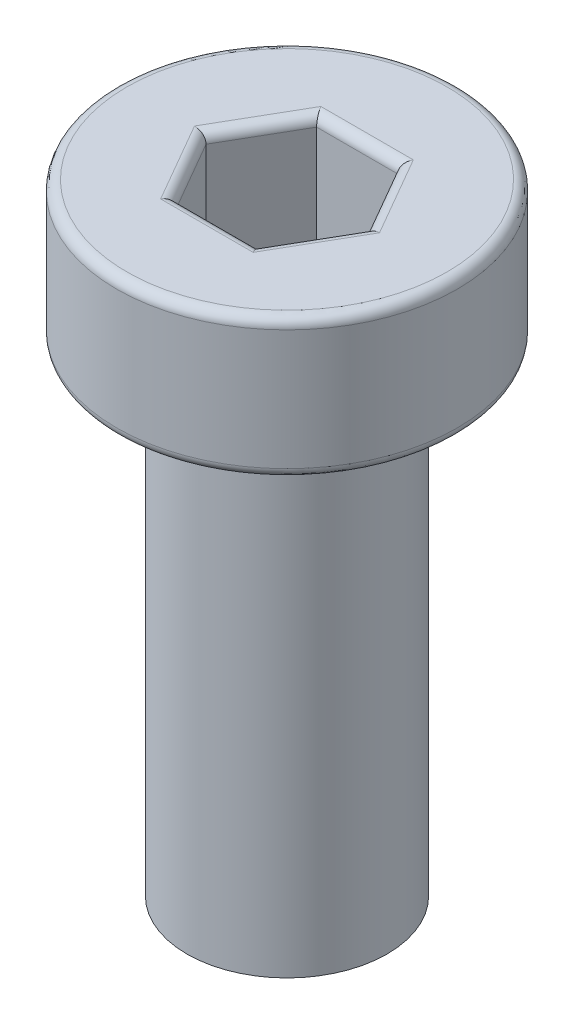
SolidWorks part; units mm, degrees
ref_plane "Front Plane" through (0, 0, 0) normal (0, 0, 1) x (1, 0, 0)
ref_plane "Top Plane" through (0, 0, 0) normal (0, 1, 0) x (1, 0, 0)
ref_plane "Right Plane" through (0, 0, 0) normal (1, 0, 0) x (0, 0, -1)
sketch "Sketch1" plane through (0, 0, 0) normal (0, 0, 1) x (1, 0, 0)
  line L0 (0, 21.3223) -> (0, -43.638) construction
sketch "Sketch2" plane through (0, 0, 0) normal (0, 0, 1) x (1, 0, 0)
  line L0 (0, 3.5) -> (4.25, 3.5)
  line L1 (0, 200021.3223) -> (0, -200043.638) construction
  line L2 (4.25, 3.5) -> (4.25, 0)
  line L3 (4.25, 0) -> (2.5, 0)
  line L4 (2.5, 0) -> (2.5, -12)
  line L5 (2.5, -12) -> (0, -12)
  line L6 (0, -12) -> (0, 3.5)
  dimension "D1" = 2.5
  dimension "D2" = 4.25
  dimension "D3" = 3.5
  dimension "D4" = 12
revolve "Revolve1" add sketch "Sketch2" angle 360 about L0
sketch "Sketch3" plane through (0, 3.5, 0) normal (0, 1, 0) x (1, 0, 0)
  line L0 (0, 0) -> (2.0207, 0) construction
  line L1 (2.0207, 0) -> (1.0104, 1.75)
  line L2 (1.0104, 1.75) -> (-1.0104, 1.75)
  line L3 (-1.0104, 1.75) -> (-2.0207, 0)
  line L4 (-2.0207, 0) -> (-1.0104, -1.75)
  line L5 (-1.0104, -1.75) -> (1.0104, -1.75)
  line L6 (1.0104, -1.75) -> (2.0207, 0)
  circle A0 centre (0, 0) radius 1.75 construction
  dimension "D1" = 3.5
extrude "Cut-Extrude1" cut sketch "Sketch3" against normal blind 3
fillet "Fillet1" radius 0.25 9 edges at (-2.5, 0, 0) (-4.25, 0, 0) (-4.25, 3.5, 0) (0, 3.5, -1.75) (-1.5155, 3.5, -0.875) (-1.5155, 3.5, 0.875) (0, 3.5, 1.75) (1.5155, 3.5, 0.875) (1.5155, 3.5, -0.875)
